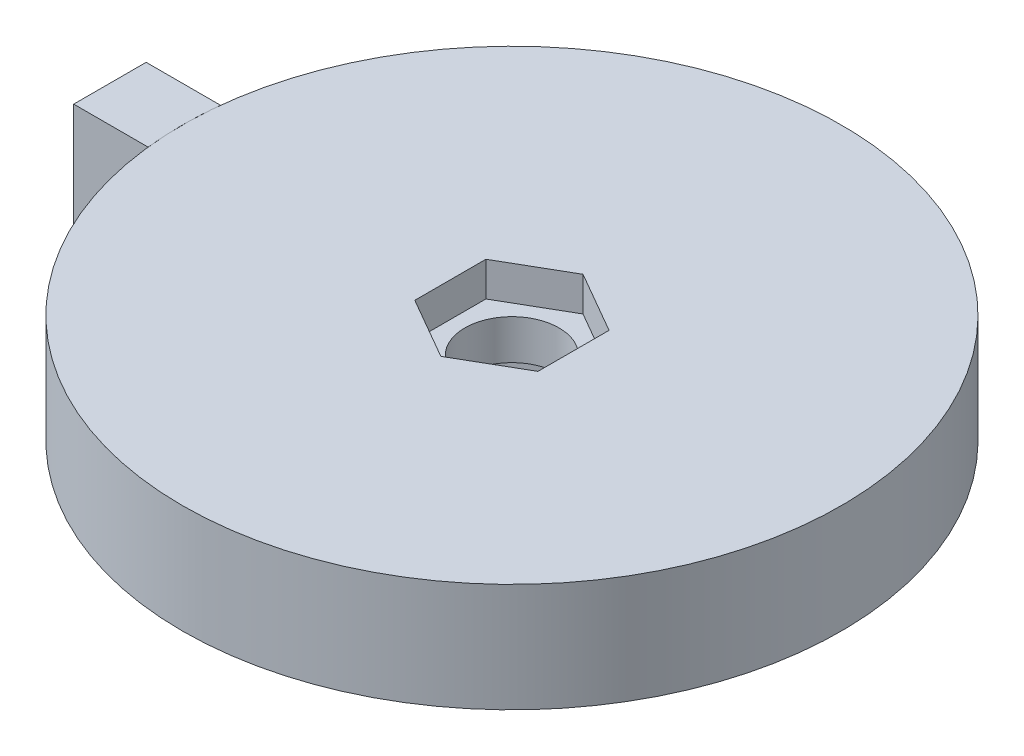
SolidWorks part; units mm, degrees
ref_plane "Plan de face" through (0, 0, 0) normal (0, 0, 1) x (1, 0, 0)
ref_plane "Plan de dessus" through (0, 0, 0) normal (0, 1, 0) x (1, 0, 0)
ref_plane "Plan de droite" through (0, 0, 0) normal (1, 0, 0) x (0, 0, -1)
sketch "Esquisse1" plane through (0, 0, 0) normal (0, 1, 0) x (1, 0, 0)
  circle A0 centre (0, 0) radius 45.5
  dimension "D1" = 91
extrude "Boss.-Extru.1" add sketch "Esquisse1" along normal blind 15
sketch "Esquisse2" plane through (0, 0, 0) normal (0, -1, 0) x (1, 0, 0)
  line L0 (-45.5, 0) -> (-55.5, 0)
  line L1 (-55.5, 0) -> (-55.5, -5)
  line L2 (-55.5, 0) -> (-55.5, 5)
  line L3 (-55.5, 5) -> (-45.2244, 5)
  line L4 (-55.5, -5) -> (-45.2244, -5)
  line L5 (-45.2244, -5) -> (-45.2244, 5)
  circle A0 centre (0, 0) radius 45.5 construction
  circle M4 centre (0, 0) radius 45.5
  dimension "D1" = 10
  dimension "D2" = 5
extrude "Boss.-Extru.2" add sketch "Esquisse2" against normal blind 15 separate body contours L1 L4 L0 M4 | L3 L2 L0 M4
sketch "Esquisse3" plane through (0, 15, 0) normal (0, 1, 0) x (1, 0, 0)
  circle A0 centre (0, 0) radius 6.5
  dimension "D1" = 13
extrude "Enlèv. mat.-Extru.1" cut sketch "Esquisse3" against normal through all contours A0
sketch "Esquisse4" plane through (0, 15, 0) normal (0, 1, 0) x (1, 0, 0)
  line L12 (-4, 6.9282) -> (-8, 4.6188)
  line L13 (-8, 4.6188) -> (-8, 0)
  line L14 (-8, 0) -> (-8, -4.6188)
  line L15 (-8, -4.6188) -> (-4, -6.9282)
  line L16 (-4, -6.9282) -> (0, -9.2376)
  line L17 (0, -9.2376) -> (4, -6.9282)
  line L18 (4, -6.9282) -> (8, -4.6188)
  line L19 (8, -4.6188) -> (8, 0)
  line L20 (8, 0) -> (8, 4.6188)
  line L21 (8, 4.6188) -> (4, 6.9282)
  line L22 (4, 6.9282) -> (0, 9.2376)
  line L23 (0, 9.2376) -> (-4, 6.9282)
  line L24 (4.25, 7.3612) -> (0, 9.815)
  line L25 (0, 9.815) -> (-4.25, 7.3612)
  line L26 (-4.25, 7.3612) -> (-8.5, 4.9075)
  line L27 (-8.5, 4.9075) -> (-8.5, 0)
  line L28 (-8.5, 0) -> (-8.5, -4.9075)
  line L29 (-8.5, -4.9075) -> (-4.25, -7.3612)
  line L30 (-4.25, -7.3612) -> (0, -9.815)
  line L31 (0, -9.815) -> (4.25, -7.3612)
  line L32 (4.25, -7.3612) -> (8.5, -4.9075)
  line L33 (8.5, -4.9075) -> (8.5, 0)
  line L34 (8.5, 0) -> (8.5, 4.9075)
  line L35 (8.5, 4.9075) -> (4.25, 7.3612)
  dimension "D1" = 0.5
extrude "Enlèv. mat.-Extru.3" cut sketch "Esquisse4" against normal blind 4.75 contours L35 L24 L25 L26 L27 L28 L29 L30 L31 L32 L33 L34
sketch "Esquisse5" plane through (0, 0, 0) normal (0, -1, 0) x (1, 0, 0)
  line L0 (-8.5, 4.9075) -> (0, 9.815) construction
  line L1 (0, 9.815) -> (8.5, 4.9075) construction
  line L2 (8.5, 4.9075) -> (8.5, -4.9075) construction
  line L3 (8.5, -4.9075) -> (0, -9.815) construction
  line L4 (0, -9.815) -> (-8.5, -4.9075) construction
  line L5 (-8.5, -4.9075) -> (-8.5, 4.9075) construction
  line L6 (-8.5, 4.9075) -> (0, 9.815)
  line L7 (0, 9.815) -> (8.5, 4.9075)
  line L8 (8.5, 4.9075) -> (8.5, -4.9075)
  line L9 (8.5, -4.9075) -> (0, -9.815)
  line L10 (0, -9.815) -> (-8.5, -4.9075)
  line L11 (-8.5, -4.9075) -> (-8.5, 4.9075)
extrude "Enlèv. mat.-Extru.4" cut sketch "Esquisse5" against normal blind 4.75 contours L11 L6 L7 L8 L9 L10
